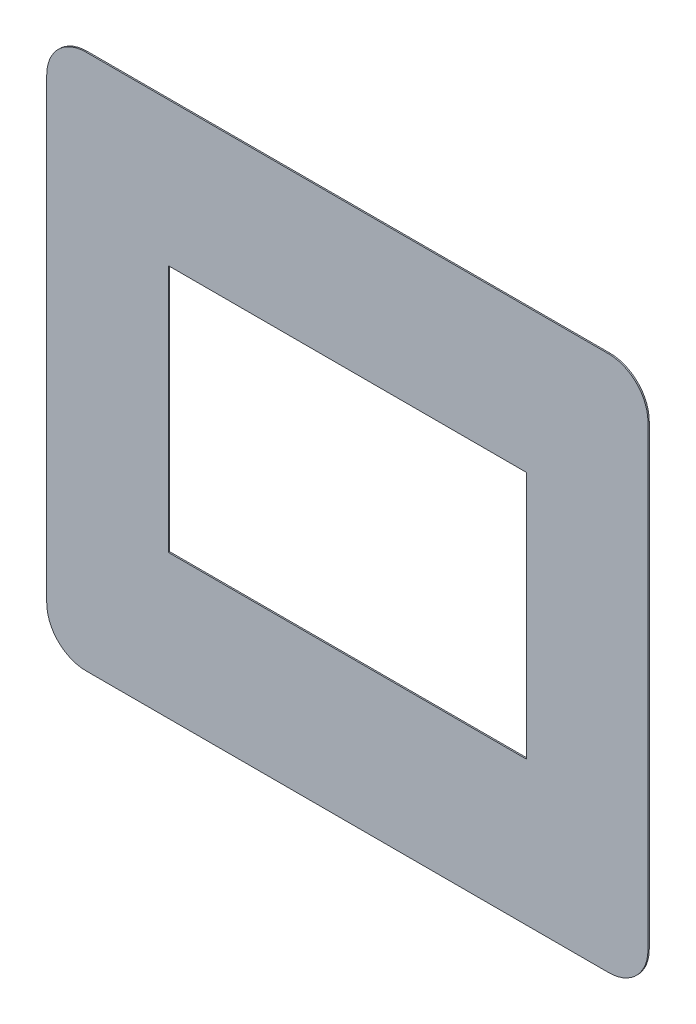
SolidWorks part; units mm, degrees
material "PE Alta Densidade"
ref_plane "Plano frontal" through (0, 0, 0) normal (0, 0, 1) x (1, 0, 0)
ref_plane "Plano superior" through (0, 0, 0) normal (0, 1, 0) x (1, 0, 0)
ref_plane "Plano direito" through (0, 0, 0) normal (1, 0, 0) x (0, 0, -1)
sketch "Esboço1" plane through (0, 0, 0) normal (0, 0, 1) x (1, 0, 0)
  line L0 (-22.1582, 19.0252) -> (-22.1582, -15.9748)
  line L1 (-19.1582, -18.9748) -> (20.8418, -18.9748)
  line L2 (23.8418, -15.9748) -> (23.8418, 19.0252)
  line L3 (20.8418, 22.0252) -> (-19.1582, 22.0252)
  arc A0 (-22.1582, 19.0252) -> (-19.1582, 22.0252) centre (-19.1582, 19.0252) cw
  arc A1 (20.8418, 22.0252) -> (23.8418, 19.0252) centre (20.8418, 19.0252) cw
  arc A2 (23.8418, -15.9748) -> (20.8418, -18.9748) centre (20.8418, -15.9748) cw
  arc A3 (-19.1582, -18.9748) -> (-22.1582, -15.9748) centre (-19.1582, -15.9748) cw
extrude "Ressalto-extrusão1" add sketch "Esboço1" along normal blind 0.1
sketch "Esboço2" plane through (0, 0, 0) normal (0, 0, -1) x (-1, 0, 0)
  line L0 (-20.8418, 22.0252) -> (19.1582, 22.0252) construction
  line L10 (-14.5418, 11.0252) -> (12.8582, 11.0252)
  line L11 (12.8582, 11.0252) -> (12.8582, -7.9748)
  line L12 (12.8582, -7.9748) -> (-14.5418, -7.9748)
  line L13 (-14.5418, -7.9748) -> (-14.5418, 11.0252)
  line L15 (22.1582, 19.0252) -> (22.1582, -15.9748) construction
  dimension "D1" = 27.4
  dimension "D2" = 19
  dimension "D3" = 9.3
  dimension "7.5" = 11
extrude "Corte-extrusão1" cut sketch "Esboço2" against normal through all both and the other way through all
